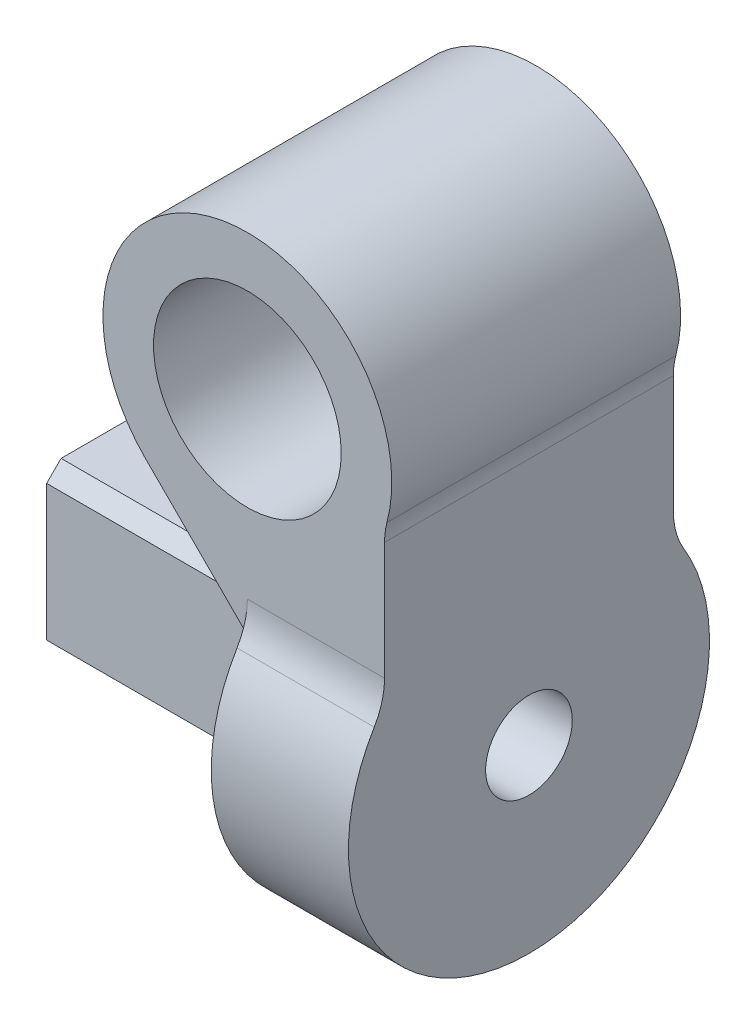
SolidWorks part; units mm, degrees
ref_plane "Front Plane" through (0, 0, 0) normal (0, 0, 1) x (1, 0, 0)
ref_plane "Top Plane" through (0, 0, 0) normal (0, 1, 0) x (1, 0, 0)
ref_plane "Right Plane" through (0, 0, 0) normal (1, 0, 0) x (0, 0, -1)
sketch "Sketch1" plane through (0, 0, 0) normal (1, 0, 0) x (0, 0, -1)
  circle A0 centre (0, 0) radius 62.5
  circle A1 centre (0, 0) radius 15
  dimension "D1" = 125
  dimension "D2" = 30
extrude "Boss-Extrude1" add sketch "Sketch1" along normal blind 47.5
sketch "Sketch2" plane through (0, 0, 0) normal (0, 0, 1) x (1, 0, 0)
  line L1 (0, 0) -> (0, 105) construction
  line L2 (-35.3553, 69.6447) -> (0, 34.2893)
  line L3 (0, 34.2893) -> (0, 55)
  arc A0 (0, 55) -> (-35.3553, 69.6447) centre (0, 105) ccw
  circle A1 centre (0, 105) radius 32.5
  arc A2 (-35.3553, 69.6447) -> (0, 55) centre (0, 105) ccw construction
  dimension "D1" = 100
  dimension "D2" = 65
  dimension "D3" = 105
  dimension "D4" = 45
extrude "Boss-Extrude2" add sketch "Sketch2" along normal mid plane 100
sketch "Sketch3" plane through (47.5, 0, 0) normal (1, 0, 0) x (0, 0, -1)
  line L0 (-50, 55) -> (-50, 62.5)
  line L1 (-50, 155) -> (-50, 55) construction
  line L2 (-50, 55) -> (-50, 37.5)
  line L3 (-29.6859, 55) -> (-50, 55)
  line L4 (-50, 55) -> (-50, 37.5)
  line L6 (50, 55) -> (29.6859, 55)
  line L7 (50, 37.5) -> (50, 55)
  line L9 (50, 37.5) -> (50, 55)
  line L10 (-50, 62.5) -> (50, 62.5)
  line L11 (50, 55) -> (50, 155) construction
  line L12 (50, 62.5) -> (50, 55)
  line L13 (29.6859, 55) -> (-29.6859, 55)
  circle A0 centre (0, 0) radius 62.5 construction
  arc A1 (-29.6859, 55) -> (-50, 37.5) centre (0, 0) ccw
  arc A2 (-29.6859, 55) -> (-50, 37.5) centre (0, 0) ccw
  arc A3 (50, 37.5) -> (29.6859, 55) centre (0, 0) ccw
  arc A4 (50, 37.5) -> (29.6859, 55) centre (0, 0) ccw
  dimension "D1" = 0
  dimension "D2" = 0
extrude "Boss-Extrude3" add sketch "Sketch3" against normal up to surface (47.5 mm away) up to face at (0, 49.5341, 43.5451)
sketch "Sketch4" plane through (0, 0, 50) normal (0, 0, 1) x (1, 0, 0)
  line L0 (47.5, 62.5) -> (47.5, 89.3875)
  line L1 (26.3391, 62.5) -> (47.5, 62.5) construction
  line L2 (26.3391, 62.5) -> (47.5, 62.5)
  arc A0 (26.3391, 62.5) -> (-35.3553, 69.6447) centre (0, 105) ccw construction
  arc A1 (26.3391, 62.5) -> (-35.3553, 69.6447) centre (0, 105) ccw
  line M2 (47.5, 62.5) -> (26.3391, 62.5)
  arc M3 (26.3391, 62.5) -> (-35.3553, 69.6447) centre (0, 105) ccw
extrude "Boss-Extrude4" add sketch "Sketch4" against normal up to surface (100 mm away) contours L0 M2 M3
fillet "Fillet1" radius 25 3 edges at (23.75, 37.5, -50) (23.75, 37.5, 50) (47.5, 89.3875, 0)
sketch "Sketch5" plane through (0, 0, 0) normal (-1, 0, 0) x (0, 0, 1)
  line L1 (-28.5, -28.5) -> (28.5, -28.5)
  line L2 (-28.5, -28.5) -> (-28.5, 28.5)
  line L3 (-28.5, 28.5) -> (28.5, 28.5)
  line L4 (28.5, -28.5) -> (28.5, 28.5)
  line L5 (-28.5, -28.5) -> (28.5, 28.5) construction
  line L6 (-28.5, 28.5) -> (28.5, -28.5) construction
  point P0 (0, 0)
  dimension "D1" = 57
extrude "Boss-Extrude5" add sketch "Sketch5" along normal blind 91
chamfer "Chamfer1" distance 5 angle 45 4 edges at (-45.5, -28.5, 28.5) (-45.5, -28.5, -28.5) (-45.5, 28.5, 28.5) (-45.5, 28.5, -28.5)
